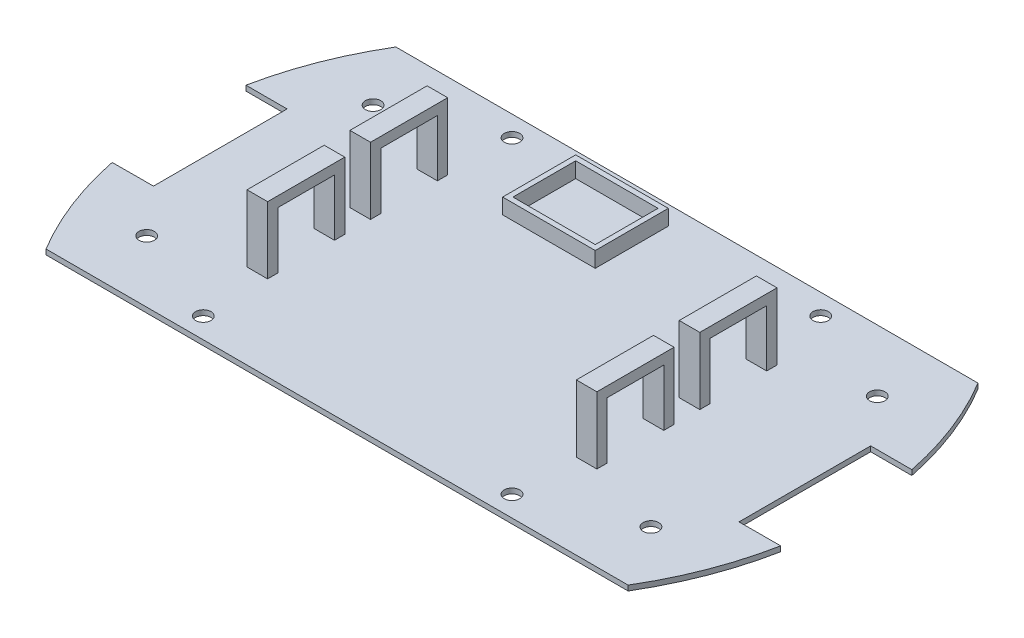
SolidWorks part; units mm, degrees
ref_plane "前基準面" through (0, 0, 0) normal (0, 0, 1) x (1, 0, 0)
ref_plane "上基準面" through (0, 0, 0) normal (0, 1, 0) x (1, 0, 0)
ref_plane "右基準面" through (0, 0, 0) normal (1, 0, 0) x (0, 0, -1)
sketch "草圖7" plane through (0, 0, 0) normal (0, 1, 0) x (1, 0, 0)
  line L1 (-34, 34) -> (34, 34)
  line L2 (-34, 34) -> (-34, -34)
  line L3 (-34, -34) -> (34, -34)
  line L4 (34, 34) -> (34, -34)
  line L5 (-34, 34) -> (34, -34) construction
  line L6 (-34, -34) -> (34, 34) construction
  point P0 (0, 0)
  point P7 (-30, 30)
  point P10 (30, 30)
  point P11 (30, -30)
  point P12 (-30, -30)
  point P13 (0, 0)
  dimension "D1" = 68
  dimension "D2" = 4
  dimension "D3" = 4
sketch "草圖10" plane through (0, 0, 0) normal (0, 1, 0) x (1, 0, 0)
  line L0 (-56.5685, 34) -> (56.5685, 34)
  line L1 (-34, 34) -> (34, 34) construction
  line L2 (-56.5685, -34) -> (56.5685, -34)
  line L3 (-34, -34) -> (34, -34) construction
  line L4 (-34, 34) -> (-34, -34) construction
  line L5 (0, 0) -> (0, 19.0172) construction
  line L6 (0, 0) -> (-12.2861, 0) construction
  line L7 (-56.707, 13) -> (-56.707, -13)
  line L8 (-64.707, 13) -> (64.707, 13)
  line L9 (56.707, 13) -> (56.707, -13)
  line L10 (-64.707, -13) -> (64.7924, -12.5675)
  arc A0 (-64.707, -13) -> (-56.5685, -34) centre (0, 0) ccw
  arc A3 (-56.5685, 34) -> (-64.707, 13) centre (0, 0) ccw
  arc A4 (64.707, 13) -> (56.5685, 34) centre (0, 0) ccw
  arc A5 (56.5685, -34) -> (64.7924, -12.5675) centre (0, 0) ccw
  point P12 (-49, 22)
  point P24 (56.707, 0)
  point P27 (-56.707, 0)
  dimension "D1" = 8
  dimension "D2" = 13
  dimension "D4" = 15
  dimension "D5" = 12
extrude "填料-伸長2" add sketch "草圖10" along normal blind 1
hole_wizard "Ø3.0mm 定位孔1" positions "3D草圖2" profile "草圖13" hole size "Ø3.0" standard "JIS"
sketch3d "3D草圖2"
  point P0 (-30, 0, -30)
  point P3 (-30, 1, -30)
  point P5 (-30, 1, 30)
  point P11 (30, 1, -30)
  point P13 (30, 1, 30)
sketch "草圖13" plane through (30, 1, 30) normal (1, 0, 0) x (0, 0, 1)
  line L0 (0, 0) -> (0, 4.9013)
  line L1 (0, 4.9013) -> (1.5, 4)
  line L2 (1.5, 4) -> (1.5, 0)
  line L5 (1.5, 0) -> (0, 0)
  line L10 (0, 4.9013) -> (-1.5, 4) construction
  line L11 (0, -6.35) -> (0, 107.95) construction
  dimension "鑽孔直徑" = 3
  dimension "鑽孔深度" = 4
  dimension "導頭角度" = 118
hole_wizard "Ø3.0mm 定位孔2" positions "3D草圖3" profile "草圖14" hole size "Ø3.0" standard "JIS"
sketch3d "3D草圖3"
  point P0 (-49, 1, -22)
sketch "草圖14" plane through (-49, 1, -22) normal (1, 0, 0) x (0, 0, 1)
  line L0 (0, 0) -> (0, 4.9013)
  line L1 (0, 4.9013) -> (1.5, 4)
  line L2 (1.5, 4) -> (1.5, 0)
  line L5 (1.5, 0) -> (0, 0)
  line L10 (0, 4.9013) -> (-1.5, 4) construction
  line L11 (0, -6.35) -> (0, 107.95) construction
  dimension "鑽孔直徑" = 3
  dimension "鑽孔深度" = 4
  dimension "導頭角度" = 118
pattern_linear "直線複製排列1" count 2 spacing 98 along (1, 0, 0) count 2 spacing 44 along (0, 0, 1) of "Ø3.0mm 定位孔2"
sketch "草圖15" plane through (0, 1, 0) normal (0, 1, 0) x (1, 0, 0)
  line L1 (-64.6001, 5.5) -> (55.3999, 5.5)
  line L2 (-64.6001, 5.5) -> (-64.6001, -5.5)
  line L3 (-64.6001, -5.5) -> (55.3999, -5.5)
  line L4 (55.3999, 5.5) -> (55.3999, -5.5)
  line L5 (-64.6001, 5.5) -> (55.3999, -5.5) construction
  line L6 (-64.6001, -5.5) -> (55.3999, 5.5) construction
  point P0 (-4.6001, 0)
  dimension "D1" = 11
  dimension "D2" = 120
sketch "草圖16" plane through (0, 1, 0) normal (0, 1, 0) x (1, 0, 0)
  line L0 (0, 0) -> (-16.1406, 0) construction
  line L1 (-34, 17.5) -> (-30, 17.5)
  line L2 (-34, 17.5) -> (-34, 2.5)
  line L3 (-34, 2.5) -> (-30, 2.5)
  line L4 (-30, 17.5) -> (-30, 2.5)
  line L5 (-34, 17.5) -> (-30, 2.5) construction
  line L6 (-34, 2.5) -> (-30, 17.5) construction
  line L7 (34, -17.5) -> (30, -2.5) construction
  line L8 (0, 10) -> (0, 20.5838) construction
  line L9 (34, 2.5) -> (30, 17.5) construction
  line L10 (34, 17.5) -> (30, 2.5) construction
  line L11 (30, 17.5) -> (30, 2.5)
  line L12 (34, 2.5) -> (30, 2.5)
  line L13 (34, 17.5) -> (34, 2.5)
  line L14 (34, 17.5) -> (30, 17.5)
  line L15 (34, -2.5) -> (30, -17.5) construction
  line L16 (0, -10) -> (0, -20.5838) construction
  line L17 (-34, -2.5) -> (-30, -17.5) construction
  line L18 (-34, -17.5) -> (-30, -2.5) construction
  line L19 (34, -17.5) -> (30, -17.5)
  line L20 (34, -17.5) -> (34, -2.5)
  line L21 (34, -2.5) -> (30, -2.5)
  line L22 (30, -17.5) -> (30, -2.5)
  line L23 (-30, -17.5) -> (-30, -2.5)
  line L24 (-34, -2.5) -> (-30, -2.5)
  line L25 (-34, -17.5) -> (-34, -2.5)
  line L26 (-34, -17.5) -> (-30, -17.5)
  point P0 (-32, 10)
  point P14 (32, 10)
  point P25 (32, -10)
  point P26 (-32, -10)
  dimension "D1" = 4
  dimension "D2" = 15
extrude "填料-伸長3" add sketch "草圖16" along normal blind 13
sketch "草圖17" plane through (-34, 0, 0) normal (-1, 0, 0) x (0, 0, 1)
  line L0 (-5.5, 1) -> (5.5, 1) construction
  line L1 (-15.5, 12) -> (-4.5, 12)
  line L2 (-15.5, 12) -> (-15.5, 1)
  line L3 (-15.5, 1) -> (-4.5, 1)
  line L4 (-4.5, 12) -> (-4.5, 1)
  line L5 (-15.5, 12) -> (-4.5, 1) construction
  line L6 (-15.5, 1) -> (-4.5, 12) construction
  line L8 (-17.5, 14) -> (-2.5, 14) construction
  line L9 (4.5, 12) -> (15.5, 12)
  line L10 (4.5, 12) -> (4.5, 1)
  line L11 (4.5, 1) -> (15.5, 1)
  line L12 (15.5, 12) -> (15.5, 1)
  line L13 (4.5, 12) -> (15.5, 1) construction
  line L14 (4.5, 1) -> (15.5, 12) construction
  line L15 (34, 1) -> (13, 1) construction
  line L16 (2.5, 14) -> (17.5, 14) construction
  point P0 (-10, 6.5)
  point P9 (-10, 14)
  point P10 (10, 6.5)
  point P19 (10, 14)
  dimension "D1" = 11
  dimension "D2" = 11
  dimension "D3" = 11
sketch "草圖18" plane through (0, 1, 0) normal (0, 1, 0) x (1, 0, 0)
  line L1 (-16.938, 29.3173) -> (-0.938, 29.3173)
  line L2 (-16.938, 29.3173) -> (-16.938, 17.1173)
  line L3 (-16.938, 17.1173) -> (-0.938, 17.1173)
  line L4 (-0.938, 29.3173) -> (-0.938, 17.1173)
  line L5 (-16.938, 29.3173) -> (-0.938, 17.1173) construction
  line L6 (-16.938, 17.1173) -> (-0.938, 29.3173) construction
  line L7 (-17.938, 30.3173) -> (0.062, 30.3173)
  line L8 (-17.938, 30.3173) -> (-17.938, 16.1173)
  line L9 (-17.938, 16.1173) -> (0.062, 16.1173)
  line L10 (0.062, 30.3173) -> (0.062, 16.1173)
  line L11 (-17.938, 30.3173) -> (0.062, 16.1173) construction
  line L12 (-17.938, 16.1173) -> (0.062, 30.3173) construction
  point P0 (-8.938, 23.2173)
  point P5 (-8.938, 23.2173)
  point P12 (-1.8121, 24.2071)
  point P13 (-4.9491, 24.4439)
  dimension "D1" = 16
  dimension "D2" = 12.2
  dimension "D3" = 1
  dimension "D4" = 1
  dimension "D5" = 1
  dimension "D6" = 1
extrude "除料-伸長1" cut sketch "草圖17" against normal up to surface (68 mm away) up to face at (34, 7.5, -10)
extrude "填料-伸長4" add sketch "草圖18" along normal blind 3
sketch "草圖19" plane through (0, 1, 0) normal (0, 1, 0) x (1, 0, 0)
  line L1 (-105.3663, 66.0318) -> (-51.3663, 66.0318)
  line L2 (-105.3663, 66.0318) -> (-105.3663, -32.9682)
  line L3 (-105.3663, -32.9682) -> (-51.3663, -32.9682)
  line L4 (-51.3663, 66.0318) -> (-51.3663, -32.9682)
  line L5 (-105.3663, 66.0318) -> (-51.3663, -32.9682) construction
  line L6 (-105.3663, -32.9682) -> (-51.3663, 66.0318) construction
  point P0 (-78.3663, 16.5318)
  point P5 (0, 0)
  dimension "D1" = 54
  dimension "D2" = 99
